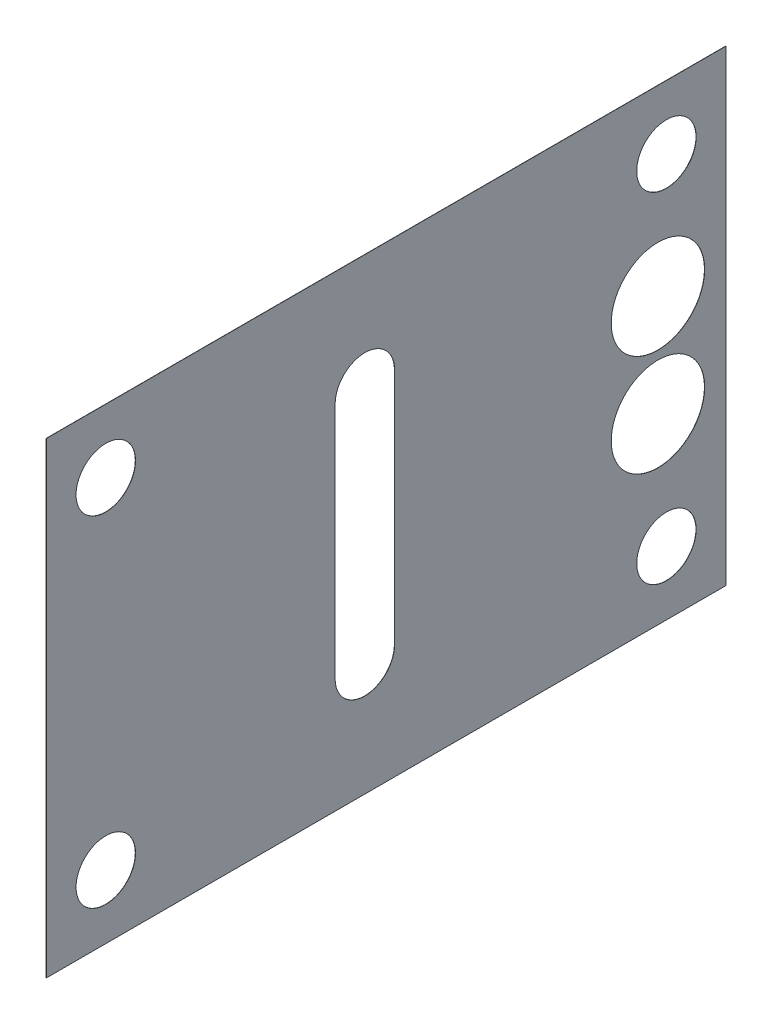
SolidWorks part; units mm, degrees
material "Low Carbon Steel"
ref_plane "Front Plane" through (0, 0, 0) normal (0, 0, 1) x (1, 0, 0)
ref_plane "Top Plane" through (0, 0, 0) normal (0, 1, 0) x (1, 0, 0)
ref_plane "Right Plane" through (0, 0, 0) normal (1, 0, 0) x (0, 0, -1)
sketch "Sketch1" plane through (0, 0, 0) normal (1, 0, 0) x (0, 0, -1)
  line L0 (-80, -55) -> (80, 55) construction
  line L1 (-80, 55) -> (80, 55)
  line L2 (-80, 55) -> (-80, -55)
  line L3 (-80, -55) -> (80, -55)
  line L4 (80, 55) -> (80, -55)
  dimension "D1" = 160
  dimension "D2" = 110
extrude "Boss-Extrude1" add sketch "Sketch1" along normal blind 0.0508
hole_wizard "M12 Clearance Hole1" positions "Sketch2" profile "Sketch3" hole size "M12" standard "Peddi DIN" end condition through all
sketch "Sketch2" plane through (0.0508, 0, 0) normal (1, 0, 0) x (0, 0, -1)
  line L0 (-66, 40) -> (66, 40) construction
  line L1 (66, 40) -> (66, -40) construction
  line L2 (66, -40) -> (-66, -40) construction
  line L3 (-66, -40) -> (66, 40) construction
  point P0 (-66, 40)
  point P2 (66, 40)
  point P4 (66, -40)
  point P6 (-66, -40)
  dimension "D1" = 80
  dimension "D2" = 132
sketch "Sketch3" plane through (0.0508, 40, 66) normal (0, 1, 0) x (0, 0, -1)
  line L0 (0, 0) -> (0, 0.0508)
  line L1 (0, 0.0508) -> (7, 0.0508)
  line L2 (7, 0.0508) -> (7, 0)
  line L5 (7, 0) -> (0, 0)
  line L11 (0, -6.35) -> (0, 107.95) construction
  dimension "Thru Hole Dia." = 14
  dimension "Thru Hole Depth" = 0.0508
sketch "Sketch4" plane through (0.0508, 0, 0) normal (1, 0, 0) x (0, 0, -1)
  line L0 (-5, 28) -> (-5, -28) construction
  line L1 (2, 28) -> (2, -28)
  line L2 (-12, 28) -> (-12, -28)
  line L3 (-5, 0) -> (0, 0) construction
  arc A0 (2, 28) -> (-12, 28) centre (-5, 28) ccw
  arc A1 (-12, -28) -> (2, -28) centre (-5, -28) ccw
  circle A2 centre (66, 40) radius 7 construction
  point P2 (-5, 0)
  dimension "D3" = 71
  dimension "D1" = 14
  dimension "D2" = 56
extrude "Cut-Extrude1" cut sketch "Sketch4" against normal through all
hole_wizard "M20 Clearance Hole1" positions "Sketch5" profile "Sketch6" hole size "M20" standard "Peddi DIN" end condition through all
sketch "Sketch5" plane through (0.0508, 0, 0) normal (1, 0, 0) x (0, 0, -1)
  line L0 (64, 12) -> (64, -12) construction
  line L2 (0, 0) -> (64, 0) construction
  circle A0 centre (66, 40) radius 7 construction
  point P0 (64, 12)
  point P5 (64, -12)
  dimension "D2" = 2
  dimension "D1" = 28
sketch "Sketch6" plane through (0.0508, 12, -64) normal (0, 1, 0) x (0, 0, -1)
  line L0 (0, 0) -> (0, 0.0508)
  line L1 (0, 0.0508) -> (11, 0.0508)
  line L2 (11, 0.0508) -> (11, 0)
  line L5 (11, 0) -> (0, 0)
  line L11 (0, -6.35) -> (0, 107.95) construction
  dimension "Thru Hole Dia." = 22
  dimension "Thru Hole Depth" = 0.0508
other "Freeze***"
